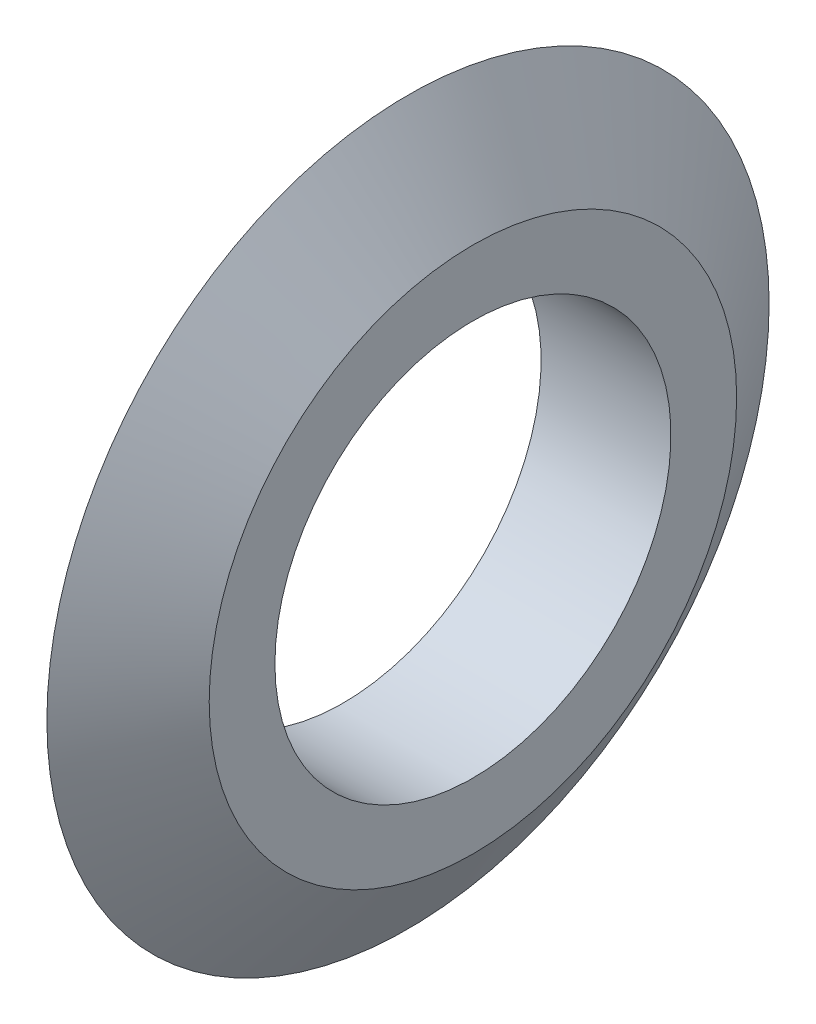
SolidWorks part; units mm, degrees
ref_plane "Front Plane" through (0, 0, 0) normal (0, 0, 1) x (1, 0, 0)
ref_plane "Top Plane" through (0, 0, 0) normal (0, 1, 0) x (1, 0, 0)
ref_plane "Right Plane" through (0, 0, 0) normal (1, 0, 0) x (0, 0, -1)
ref_axis "Axis1" through (-6.9241, 0, 0) along (1, 0, 0)
sketch "Sketch5" plane through (0, 0, 0) normal (0, 0, 1) x (1, 0, 0)
  line L0 (0, 0) -> (0, 6.1) construction
  line L1 (-2, 6.1) -> (2, 6.1)
  line L2 (-2, 6.1) -> (-2, 8.1244)
  line L3 (-2, 8.1244) -> (0, 11.1244)
  line L4 (2, 6.1) -> (2, 8.1244)
  line L5 (2, 8.1244) -> (0, 11.1244)
  point P6 (0, 6.1)
  dimension "D1" = 6.1
  dimension "D2" = 4
  dimension "D3" = 2.0244
  dimension "D4" = 3
revolve "Revolve4" add sketch "Sketch5" angle 360 about axis through (-6.9241, 0, 0) along (1, 0, 0)
